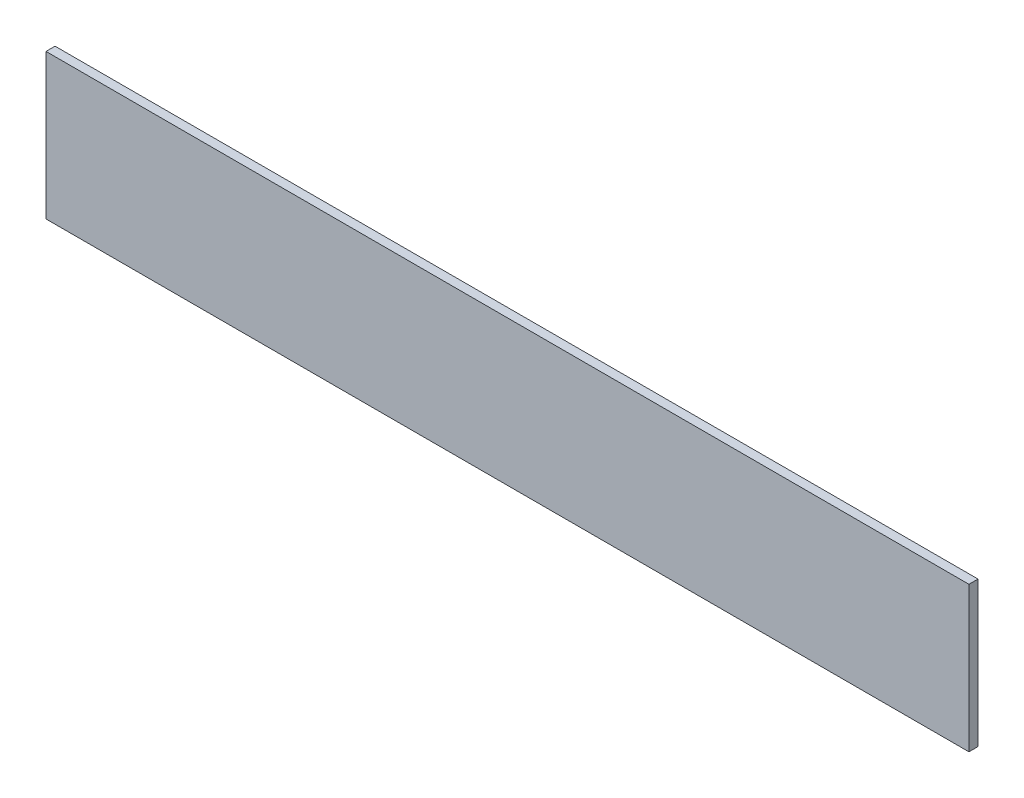
SolidWorks part; units mm, degrees
ref_plane "Front Plane" through (0, 0, 0) normal (0, 0, 1) x (1, 0, 0)
ref_plane "Top Plane" through (0, 0, 0) normal (0, 1, 0) x (1, 0, 0)
ref_plane "Right Plane" through (0, 0, 0) normal (1, 0, 0) x (0, 0, -1)
sketch "Sketch1" plane through (0, 0, 0) normal (0, 0, 1) x (1, 0, 0)
  line L0 (0, 0) -> (0, 101.6) construction
  line L1 (0, 0) -> (646.2163, 0)
  line L2 (0, 0) -> (0, 101.6)
  line L3 (0, 101.6) -> (646.2163, 101.6)
  line L4 (646.2163, 0) -> (646.2163, 101.6)
  line L5 (646.2163, 0) -> (646.2163, 101.6) construction
  dimension "D1" = 101.6
extrude "Boss-Extrude1" add sketch "Sketch1" along normal blind 6.35
